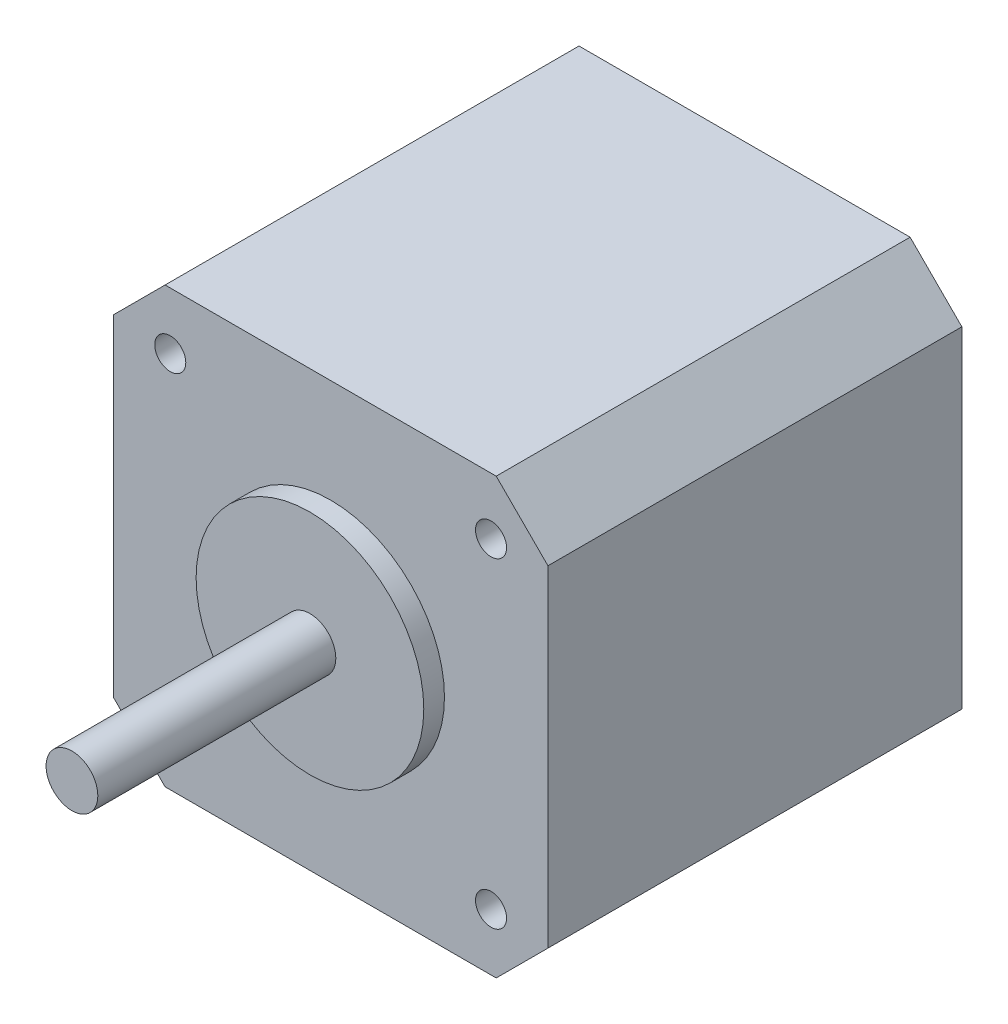
SolidWorks part; units mm, degrees
ref_plane "前基準面" through (0, 0, 0) normal (0, 0, 1) x (1, 0, 0)
ref_plane "上基準面" through (0, 0, 0) normal (0, 1, 0) x (1, 0, 0)
ref_plane "右基準面" through (0, 0, 0) normal (1, 0, 0) x (0, 0, -1)
sketch "草圖1" plane through (0, 0, 0) normal (0, 0, 1) x (1, 0, 0)
  line L1 (-21, 21) -> (21, 21)
  line L2 (-21, 21) -> (-21, -21)
  line L3 (-21, -21) -> (21, -21)
  line L4 (21, 21) -> (21, -21)
  point P4 (0, 21)
  point P6 (-21, 0)
  dimension "D1" = 42
  dimension "D2" = 42
extrude "填料-伸長1" add sketch "草圖1" along normal blind 40
chamfer "導角1" distance 5 angle 45 4 edges at (-21, -21, 20) (21, -21, 20) (21, 21, 20) (-21, 21, 20)
sketch "草圖2" plane through (0, 0, 40) normal (0, 0, 1) x (1, 0, 0)
  circle A0 centre (0, 0) radius 11
  dimension "D1" = 22
extrude "填料-伸長2" add sketch "草圖2" along normal blind 2
sketch "草圖3" plane through (0, 0, 42) normal (0, 0, 1) x (1, 0, 0)
  circle A0 centre (0, 0) radius 2.5
  dimension "D1" = 5
extrude "填料-伸長3" add sketch "草圖3" along normal blind 23
sketch "草圖4" plane through (0, 0, 40) normal (0, 0, 1) x (1, 0, 0)
  line L0 (-21, 16) -> (-21, -16) construction
  line L1 (16, 21) -> (-16, 21) construction
  line L2 (0, 21) -> (0, -21) construction
  line L3 (-16, -21) -> (16, -21) construction
  line L4 (0, -21) -> (21, 0) construction
  line L5 (21, -16) -> (21, 16) construction
  line L6 (21, 0) -> (-21, 0) construction
  circle A0 centre (-15.5, 15.5) radius 1.5
  circle A1 centre (-15.5, -15.5) radius 1.5
  circle A2 centre (15.5, -15.5) radius 1.5
  circle A3 centre (15.5, 15.5) radius 1.5
  dimension "D1" = 3
  dimension "D2" = 5.5
  dimension "D3" = 5.5
  dimension "D4" = 31
extrude "除料-伸長1" cut sketch "草圖4" against normal blind 3
